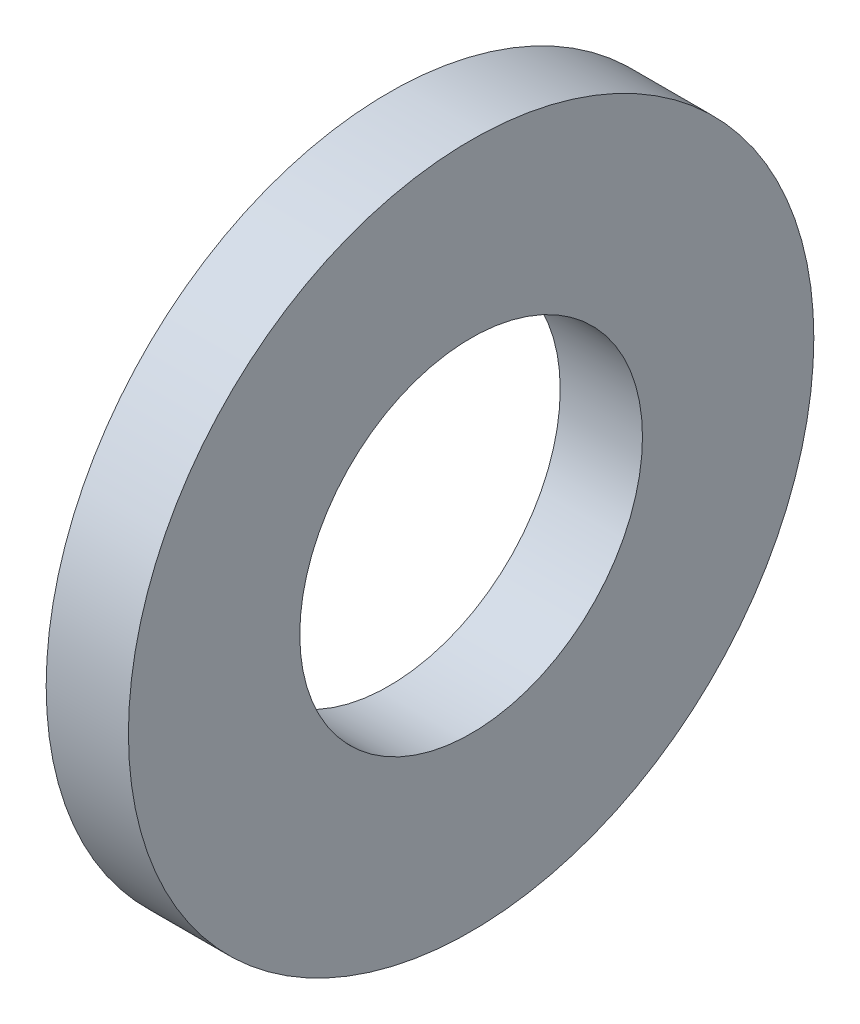
SolidWorks part; units mm, degrees
material "PET"
ref_plane "Front" through (0, 0, 0) normal (0, 0, 1) x (1, 0, 0)
ref_plane "Top" through (0, 0, 0) normal (0, 1, 0) x (1, 0, 0)
ref_plane "Right" through (0, 0, 0) normal (1, 0, 0) x (0, 0, -1)
sketch "Sketch1" plane through (0, 0, 0) normal (1, 0, 0) x (0, 0, -1)
  circle A0 centre (0, 0) radius 4.7625
  circle A1 centre (0, 0) radius 9.525
  dimension "D1" = 9.525
  dimension "D2" = 19.05
extrude "Boss-Extrude1" add sketch "Sketch1" along normal blind 2.286
